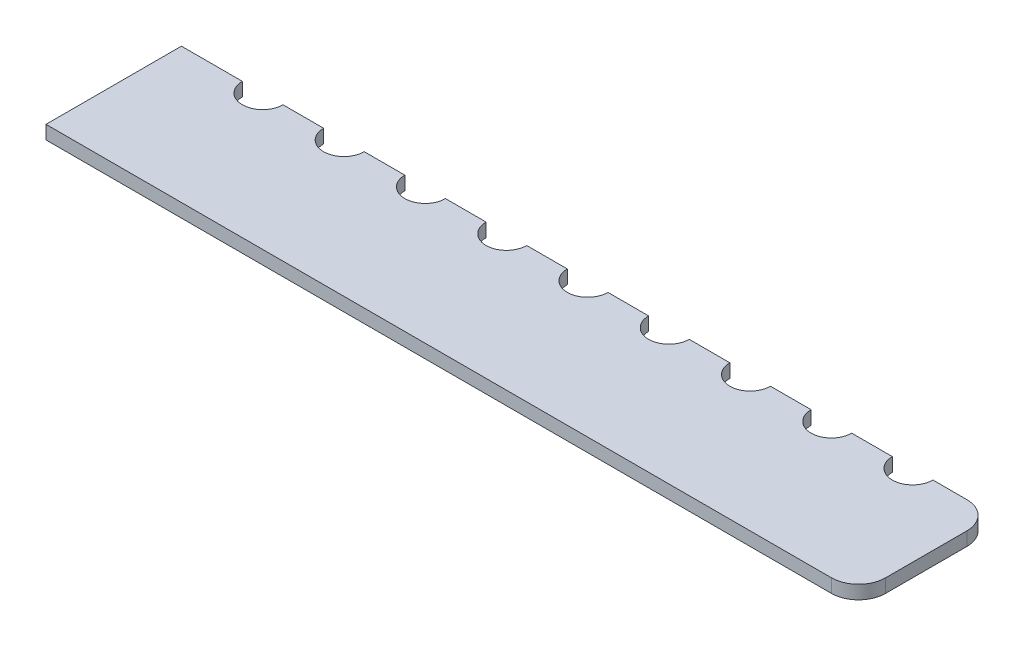
SolidWorks part; units mm, degrees
material "Plain Carbon Steel"
ref_plane "Front Plane" through (0, 0, 0) normal (0, 0, 1) x (1, 0, 0)
ref_plane "Top Plane" through (0, 0, 0) normal (0, 1, 0) x (1, 0, 0)
ref_plane "Right Plane" through (0, 0, 0) normal (1, 0, 0) x (0, 0, -1)
sketch "Sketch1" plane through (0, 0, 0) normal (0, 1, 0) x (1, 0, 0)
  line L1 (0, 0) -> (-300, 0)
  line L2 (0, 0) -> (0, 50)
  line L3 (0, 50) -> (-300, 50)
  line L4 (-300, 0) -> (-300, 50)
  dimension "D1" = 300
  dimension "D2" = 50
extrude "Boss-Extrude1" add sketch "Sketch1" along normal blind 5
sketch "Sketch2" plane through (0, 5, 0) normal (0, 1, 0) x (1, 0, 0)
  line L0 (0, 50) -> (-300, 50) construction
  circle A0 centre (-270, 50) radius 7.5
  dimension "D2" = 15
  dimension "D1" = 30
extrude "Cut-Extrude1" cut sketch "Sketch2" against normal blind 5
pattern_linear "LPattern1" count 9 spacing 30 along (1, 0, 0) of "Cut-Extrude1"
fillet "Fillet2" radius 10 2 edges at (0, 2.5, 0) (0, 2.5, -50)
other "Bounding Box"
ref_plane "Default Plane" through (-300, 5, -50) normal (0, 0, 1) x (1, 0, 0)
